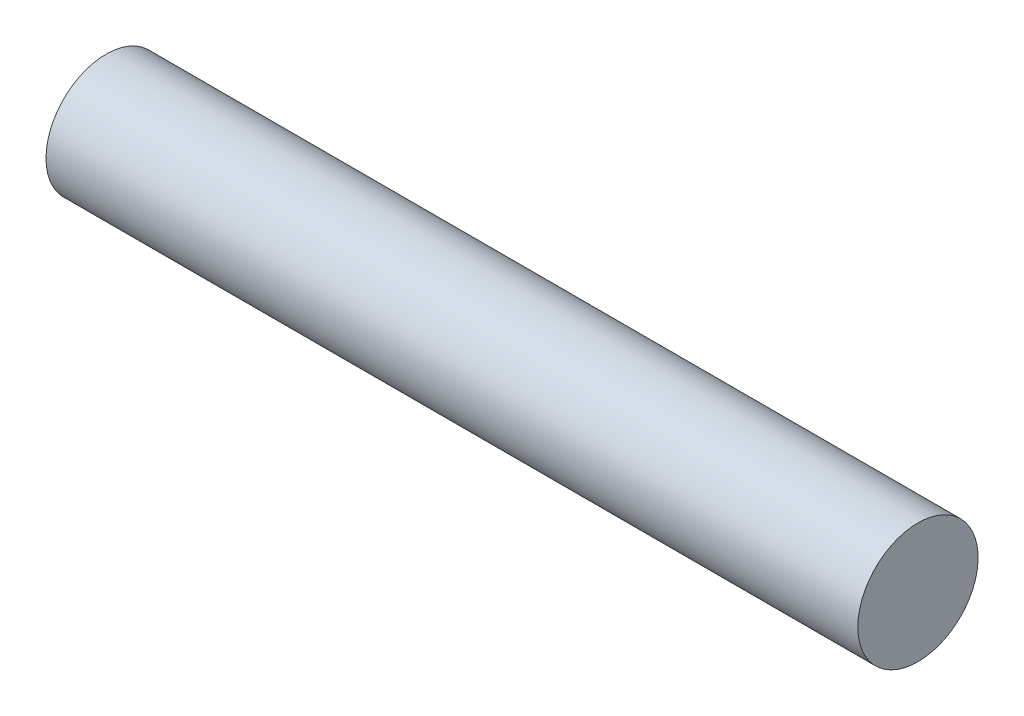
SolidWorks part; units mm, degrees
ref_plane "前视基准面" through (0, 0, 0) normal (0, 0, 1) x (1, 0, 0)
ref_plane "上视基准面" through (0, 0, 0) normal (0, 1, 0) x (1, 0, 0)
ref_plane "右视基准面" through (0, 0, 0) normal (1, 0, 0) x (0, 0, -1)
other "Configuration Table"
sketch "草图1" plane through (0, 0, 0) normal (0, 0, 1) x (1, 0, 0)
  line L0 (0, 0) -> (40.0305, 0) construction
  line L1 (0, 0) -> (0, 6)
  line L2 (0, 6) -> (81, 6)
  line L3 (81, 6) -> (81, 0)
  line L4 (0, 0) -> (81, 0)
  dimension "D1" = 6
  dimension "D2" = 81
revolve "旋转1" add sketch "草图1" angle 360 about L0
